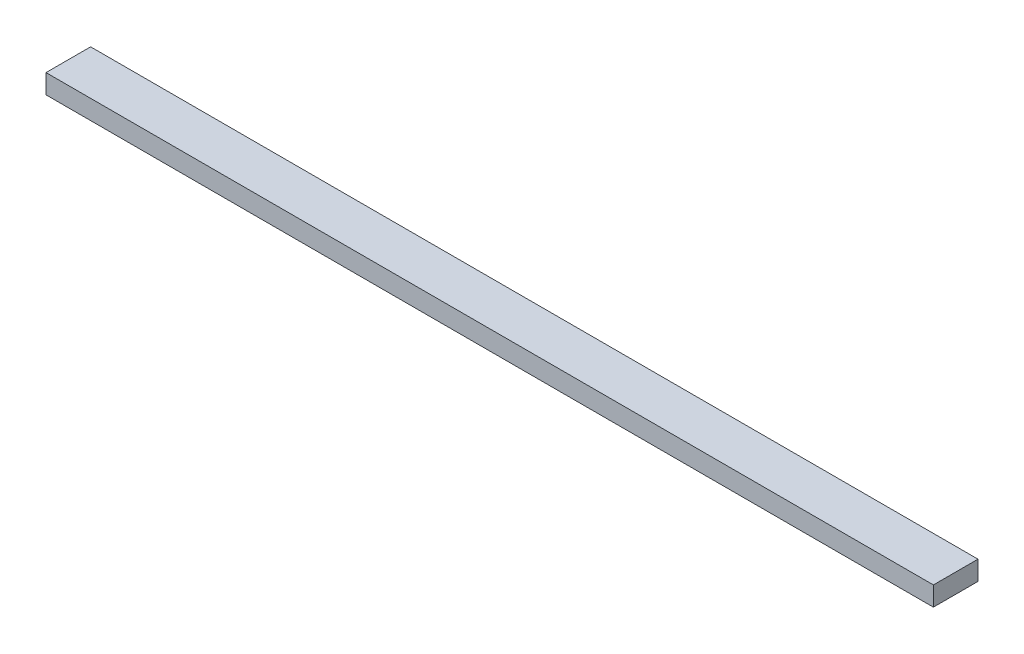
SolidWorks part; units mm, degrees
material "Pine"
ref_plane "Front Plane" through (0, 0, 0) normal (0, 0, 1) x (1, 0, 0)
ref_plane "Top Plane" through (0, 0, 0) normal (0, 1, 0) x (1, 0, 0)
ref_plane "Right Plane" through (0, 0, 0) normal (1, 0, 0) x (0, 0, -1)
sketch "Sketch1" plane through (0, 0, 0) normal (1, 0, 0) x (0, 0, -1)
  line L1 (44.0531, -19.05) -> (-44.0531, -19.05)
  line L2 (44.0531, -19.05) -> (44.0531, 19.05)
  line L3 (44.0531, 19.05) -> (-44.0531, 19.05)
  line L4 (-44.0531, -19.05) -> (-44.0531, 19.05)
  line L5 (44.0531, -19.05) -> (-44.0531, 19.05) construction
  line L6 (44.0531, 19.05) -> (-44.0531, -19.05) construction
  point P0 (0, 0)
  dimension "D1" = 88.1063
  dimension "D2" = 38.1
extrude "Boss-Extrude1" add sketch "Sketch1" along normal blind 1752.6
